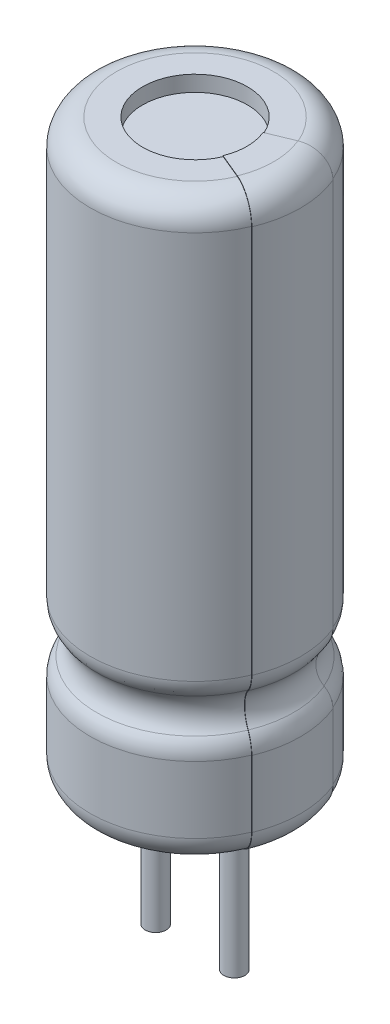
SolidWorks part; units mm, degrees
ref_plane "Front Plane" through (0, 0, 0) normal (0, 0, 1) x (1, 0, 0)
ref_plane "Top Plane" through (0, 0, 0) normal (0, 1, 0) x (1, 0, 0)
ref_plane "Right Plane" through (0, 0, 0) normal (1, 0, 0) x (0, 0, -1)
sketch "Sketch1" plane through (0, 0, 0) normal (0, 0, 1) x (1, 0, 0)
  line L0 (0, 0.3) -> (0, 10.7)
  line L1 (0, 10.7) -> (1, 10.7)
  line L2 (1, 10.7) -> (1, 11)
  line L3 (1, 11) -> (1.5, 11)
  line L4 (2, 10.5) -> (2, 3.0945)
  line L5 (2, 1.7716) -> (2, 0.5)
  line L6 (1.5, 0) -> (1, 0)
  line L7 (0, 0) -> (0, -8.1899) construction
  line L8 (0, 0.3) -> (1, 0.3)
  line L9 (1, 0.3) -> (1, 0)
  line L10 (0, 5.5) -> (1.9584, 5.5) construction
  arc A0 (1.875, 2.7637) -> (1.875, 2.1023) centre (2.25, 2.433) ccw
  arc A1 (2, 10.5) -> (1.5, 11) centre (1.5, 10.5) ccw
  arc A2 (2, 3.0945) -> (1.875, 2.7637) centre (1.5, 3.0945) cw
  arc A3 (2, 1.7716) -> (1.875, 2.1023) centre (1.5, 1.7716) ccw
  arc A4 (1.5, 0) -> (2, 0.5) centre (1.5, 0.5) ccw
  point P13 (2, 11)
  point P18 (2, 2)
  point P21 (2, 0)
  dimension "D3" = 0.5
  dimension "D5" = 0.5
  dimension "D1" = 0.3
  dimension "D2" = 1
  dimension "D4" = 2
  dimension "D" = 4
  dimension "L" = 11
  dimension "D9" = 0.25
revolve "Revolve1" add sketch "Sketch1" angle 360 about L7
sketch "Sketch2" plane through (0, 0.3, 0) normal (0, -1, 0) x (1, 0, 0)
  line L0 (-0.75, 0) -> (0, 0) construction
  line L1 (0, 0) -> (0, 0.7452) construction
  circle A0 centre (-0.75, 0) radius 0.2
  circle A1 centre (0.75, 0) radius 0.2
  dimension "d" = 0.4
  dimension "S" = 1.5
extrude "Extrude1" add sketch "Sketch2" along normal blind 3
sketch "Sketch3" plane through (0, 0, 0) normal (0, 0, 1) x (1, 0, 0)
  line L10 (0.99, 11.01) -> (0.99, -0.01)
  line L18 (-0.01, 10.71) -> (-0.01, 0.29)
  line L19 (0.99, 10.71) -> (-0.01, 10.71)
  line L20 (0.99, 11.01) -> (0.99, 10.71)
  line L21 (1.5, 11.01) -> (0.99, 11.01)
  line L22 (2.01, 3.0945) -> (2.01, 10.5)
  line L23 (2.01, 0.5) -> (2.01, 1.7716)
  line L24 (0.99, -0.01) -> (1.5, -0.01)
  line L25 (0.99, 0.29) -> (0.99, -0.01)
  line L26 (-0.01, 0.29) -> (0.99, 0.29)
  line L27 (-0.01, 10.71) -> (-0.01, 0.29) construction
  line L28 (0.99, 10.71) -> (-0.01, 10.71) construction
  line L29 (0.99, 11.01) -> (0.99, 10.71) construction
  line L30 (1.5, 11.01) -> (0.99, 11.01)
  line L31 (2.01, 3.0945) -> (2.01, 10.5)
  line L32 (2.01, 0.5) -> (2.01, 1.7716)
  line L33 (0.99, -0.01) -> (1.5, -0.01)
  line L34 (0.99, 0.29) -> (0.99, -0.01) construction
  line L35 (-0.01, 0.29) -> (0.99, 0.29) construction
  arc A10 (2.01, 10.5) -> (1.5, 11.01) centre (1.5, 10.5) ccw
  arc A11 (1.8825, 2.7571) -> (2.01, 3.0945) centre (1.5, 3.0945) ccw
  arc A12 (1.8825, 2.7571) -> (1.8825, 2.1089) centre (2.25, 2.433) ccw
  arc A13 (2.01, 1.7716) -> (1.8825, 2.1089) centre (1.5, 1.7716) ccw
  arc A14 (1.5, -0.01) -> (2.01, 0.5) centre (1.5, 0.5) ccw
  arc A15 (2.01, 10.5) -> (1.5, 11.01) centre (1.5, 10.5) ccw
  arc A16 (1.8825, 2.7571) -> (2.01, 3.0945) centre (1.5, 3.0945) ccw
  arc A17 (1.8825, 2.7571) -> (1.8825, 2.1089) centre (2.25, 2.433) ccw
  arc A18 (2.01, 1.7716) -> (1.8825, 2.1089) centre (1.5, 1.7716) ccw
  arc A19 (1.5, -0.01) -> (2.01, 0.5) centre (1.5, 0.5) ccw
  dimension "D1" = 0.01
revolve "Revolve2" add sketch "Sketch3" angle 45 mid plane about L27
